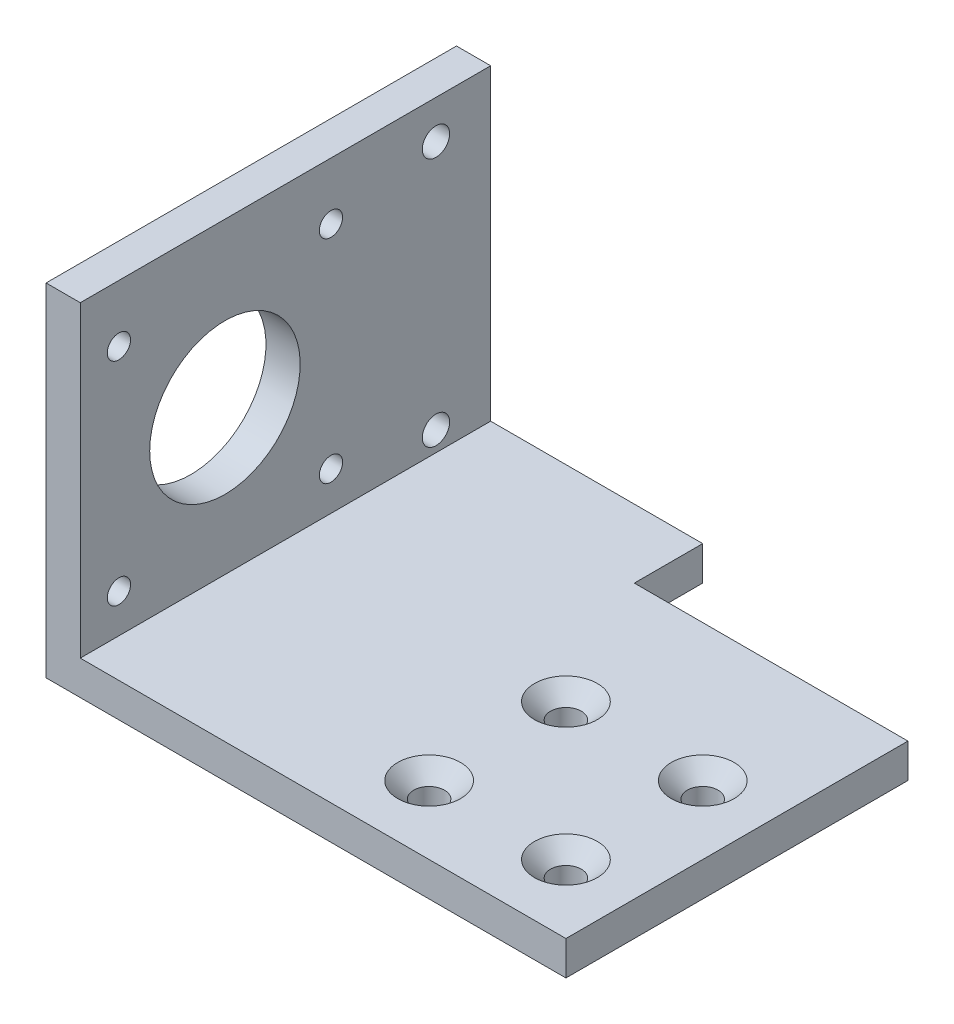
SolidWorks part; units mm, degrees
ref_plane "Спереди" through (0, 0, 0) normal (0, 0, 1) x (1, 0, 0)
ref_plane "Сверху" through (0, 0, 0) normal (0, 1, 0) x (1, 0, 0)
ref_plane "Справа" through (0, 0, 0) normal (1, 0, 0) x (0, 0, -1)
sketch "Эскиз1" plane through (0, 0, 0) normal (0, 0, 1) x (1, 0, 0)
  line L0 (0, 0) -> (0, 50)
  line L1 (0, 50) -> (5, 50)
  line L2 (5, 50) -> (5, 5)
  line L3 (5, 5) -> (95, 5)
  line L4 (95, 5) -> (95, 50)
  line L5 (95, 50) -> (100, 50)
  line L6 (100, 50) -> (100, 0)
  line L7 (100, 0) -> (0, 0)
  line L8 (5, 5) -> (5, 0) construction
  dimension "D1" = 100
  dimension "D2" = 50
  dimension "D3" = 5
extrude "Бобышка-Вытянуть1" add sketch "Эскиз1" along normal blind 60
sketch "Эскиз2" plane through (0, 0, 0) normal (-1, 0, 0) x (0, 0, 1)
  line L0 (60, 50) -> (60, 0) construction
  line L2 (60, 0) -> (0, 0) construction
  circle A0 centre (38.85, 26.15) radius 11
  dimension "D1" = 22
  dimension "D2" = 21.15
  dimension "D3" = 26.15
extrude "Вырез-Вытянуть1" cut sketch "Эскиз2" against normal blind 60
hole_wizard "CSK размера винта с полупотайной головкой и крестообразным шлицем1" positions "Эскиз4" profile "Эскиз3" countersink size "M3" standard "DIN"
sketch "Эскиз4" plane through (0, 0, 0) normal (-1, 0, 0) x (0, 0, 1)
  line L1 (23.35, 41.65) -> (54.35, 41.65)
  line L2 (23.35, 41.65) -> (23.35, 10.65)
  line L3 (23.35, 10.65) -> (54.35, 10.65)
  line L4 (54.35, 41.65) -> (54.35, 10.65)
  circle A0 centre (38.85, 26.15) radius 21.9203
  point P0 (54.35, 10.65)
  point P1 (54.35, 41.65)
  point P3 (23.35, 41.65)
  point P5 (23.35, 10.65)
  dimension "D1" = 31
sketch "Эскиз3" plane through (0, 10.65, 54.35) normal (0, 1, 0) x (0, 0, 1)
  line L0 (0, 0) -> (0, 5)
  line L1 (0, 5) -> (1.7, 5)
  line L2 (1.7, 5) -> (1.7, 1.77)
  line L3 (1.7, 1.77) -> (3.47, 0)
  line L5 (3.47, 0) -> (0, 0)
  line L6 (-1.7, 1.77) -> (-3.47, 0) construction
  line L11 (0, -6.35) -> (0, 107.95) construction
  dimension "Диаметр сквозного отверстия" = 3.4
  dimension "Глубина сквозного отверстия" = 5
  dimension "Диаметр передней зенковки" = 6.94
  dimension "Угол передней зенковки" = 90
sketch "Эскиз5" plane through (0, 0, 0) normal (0, -1, 0) x (1, 0, 0)
  line L0 (0, 60) -> (0, 0) construction
  line L1 (100, 0) -> (36, 0)
  line L2 (100, 0) -> (100, 10)
  line L3 (100, 10) -> (36, 10)
  line L4 (36, 0) -> (36, 10)
  dimension "D1" = 36
  dimension "D2" = 10
extrude "Вырез-Вытянуть2" cut sketch "Эскиз5" against normal through all
sketch "Эскиз6" plane through (0, 0, 0) normal (-1, 0, 0) x (0, 0, 1)
  line L0 (38.85, 26.15) -> (0, 26.15) construction
  line L1 (8, 44.4) -> (8, 7.9) construction
  line L2 (0, 50) -> (0, 0) construction
  circle A0 centre (8, 44.4) radius 2
  circle A1 centre (8, 7.9) radius 2
  point P5 (8, 26.15)
  dimension "D3" = 4
  dimension "D1" = 36.5
  dimension "D2" = 8
extrude "Вырез-Вытянуть3" cut sketch "Эскиз6" against normal blind 10
sketch "Эскиз7" plane through (0, 0, 0) normal (-1, 0, 0) x (0, 0, 1)
  circle A0 centre (8, 44.4) radius 3
  circle A1 centre (8, 7.9) radius 3
  dimension "D1" = 6
extrude "Вырез-Вытянуть4" cut sketch "Эскиз7" against normal blind 2
sketch "Эскиз8" plane through (0, 0, 0) normal (0, -1, 0) x (1, 0, 0)
  line L0 (0, 60) -> (100, 60) construction
  line L1 (100, 10) -> (76, 10)
  line L2 (100, 10) -> (100, 60)
  line L3 (100, 60) -> (76, 60)
  line L4 (76, 10) -> (76, 60)
  line L5 (36, 10) -> (36, 0) construction
  dimension "D1" = 40
extrude "Вырез-Вытянуть5" cut sketch "Эскиз8" against normal through all
hole_wizard "Зенковка для винта с потайной головкой и внутренним шестигранником M41" positions "Эскиз10" profile "Эскиз9" countersink size "M4" standard "DIN" end condition through all
sketch "Эскиз10" plane through (0, 5, 0) normal (0, 1, 0) x (-1, 0, 0)
  line L0 (-76, 60) -> (-76, 10) construction
  line L1 (-76, 60) -> (-5, 60) construction
  point P0 (-46, 30)
  point P1 (-66, 30)
  point P3 (-46, 50)
  point P5 (-66, 50)
  dimension "D1" = 20
  dimension "D2" = 20
  dimension "D3" = 10
  dimension "D4" = 10
sketch "Эскиз9" plane through (46, 5, 30) normal (1, 0, 0) x (0, 0, 1)
  line L0 (0, 0) -> (0, 5)
  line L1 (0, 5) -> (2.25, 5)
  line L2 (2.25, 5) -> (2.25, 2.34)
  line L3 (2.25, 2.34) -> (4.59, 0)
  line L5 (4.59, 0) -> (0, 0)
  line L6 (-2.25, 2.34) -> (-4.59, 0) construction
  line L11 (0, -6.35) -> (0, 107.95) construction
  dimension "Диаметр сквозного отверстия" = 4.5
  dimension "Глубина сквозного отверстия" = 5
  dimension "Диаметр передней зенковки" = 9.18
  dimension "Угол передней зенковки" = 90
